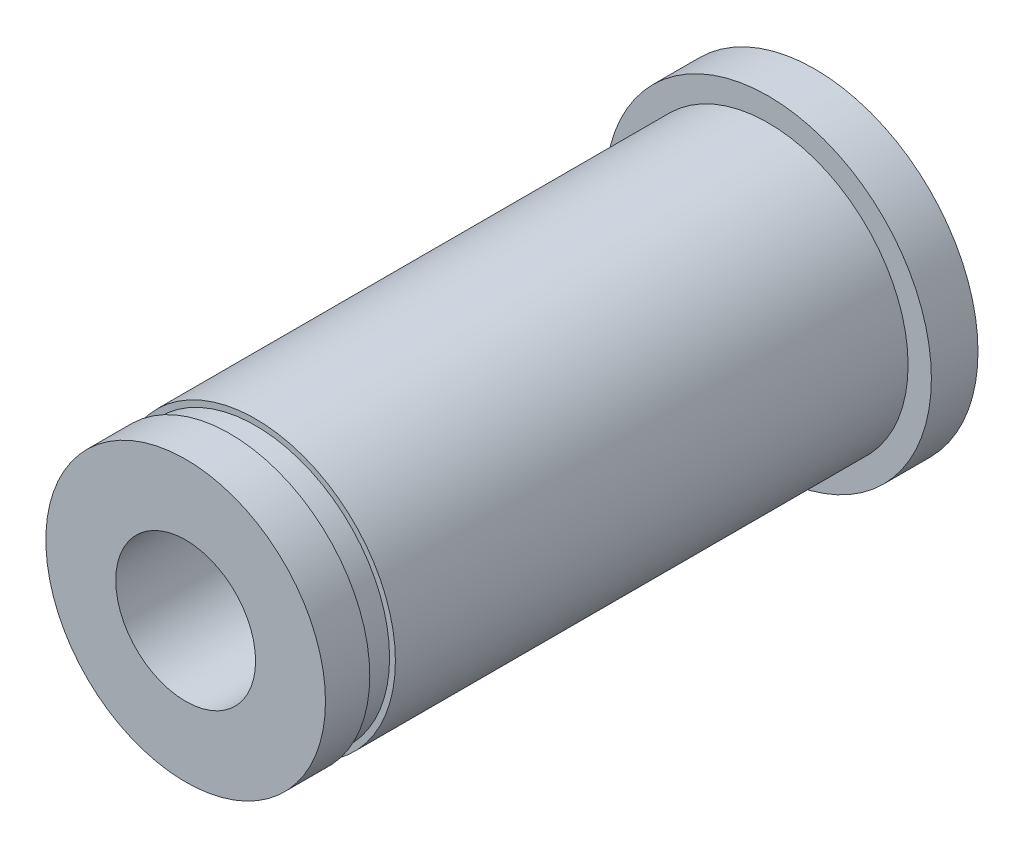
SolidWorks part; units mm, degrees
material "AISI 1045 钢，冷拔"
ref_plane "前视基准面" through (0, 0, 0) normal (0, 0, 1) x (1, 0, 0)
ref_plane "上视基准面" through (0, 0, 0) normal (0, 1, 0) x (1, 0, 0)
ref_plane "右视基准面" through (0, 0, 0) normal (1, 0, 0) x (0, 0, -1)
sketch "草图1" plane through (0, 0, 0) normal (0, 0, 1) x (1, 0, 0)
  circle A0 centre (0, 0) radius 6
  dimension "D1" = 12
extrude "凸台-拉伸1" add sketch "草图1" along normal blind 25
sketch "草图2" plane through (0, 0, 0) normal (0, 0, -1) x (-1, 0, 0)
  circle A0 centre (0, 0) radius 7
  dimension "D1" = 14
extrude "凸台-拉伸2" add sketch "草图2" along normal blind 2
sketch "草图3" plane through (0, 0, 0) normal (0, 1, 0) x (1, 0, 0)
  line L0 (-6, 0) -> (-6, -22) construction
  line L1 (0, -25) -> (0, -12.3222) construction
  line L2 (-6, -22) -> (-5.75, -22)
  line L3 (-6, -22) -> (-6, -23.1)
  line L4 (-6, -23.1) -> (-5.75, -23.1)
  line L5 (-5.75, -22) -> (-5.75, -23.1)
  line L6 (-6, -25) -> (6, -25) construction
  dimension "D1" = 22
  dimension "D2" = 1.1
  dimension "D3" = 0.25
revolve "切除-旋转1" cut sketch "草图3" angle 360 about L1
sketch "草图4" plane through (0, 0, -2) normal (0, 0, -1) x (-1, 0, 0)
  circle A0 centre (0, 0) radius 3
  dimension "D1" = 6
extrude "切除-拉伸1" cut sketch "草图4" against normal blind 28
